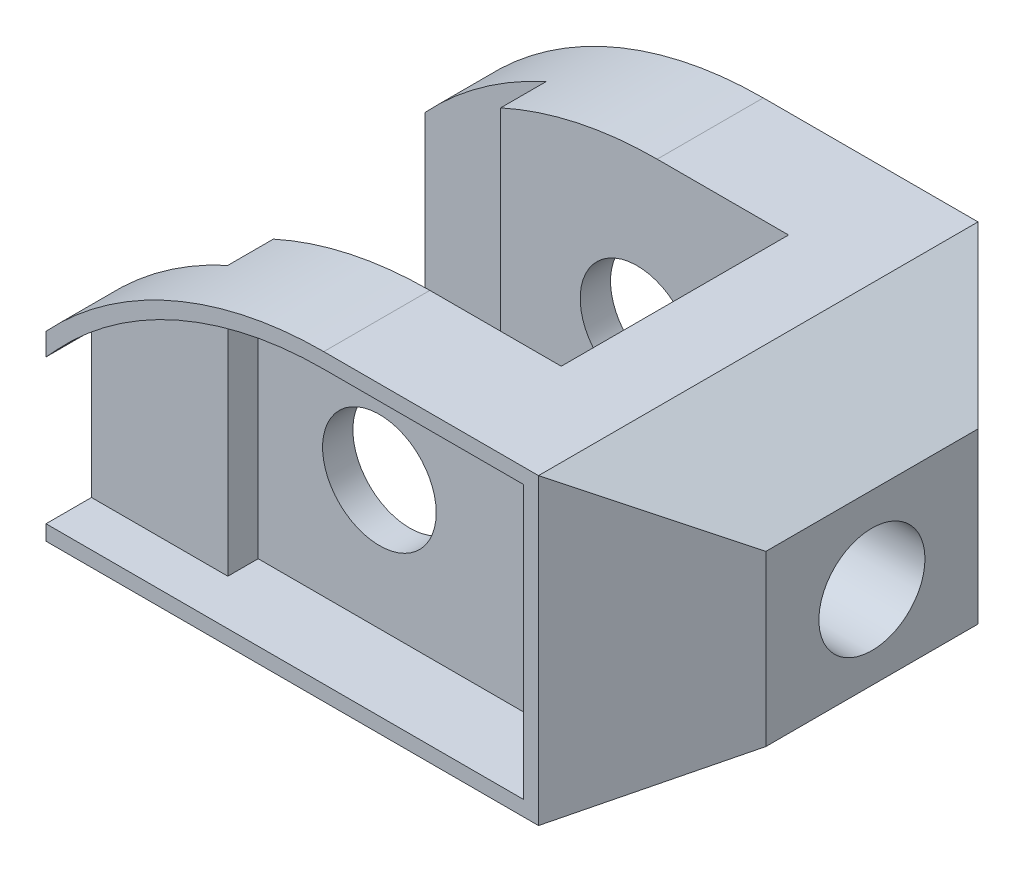
SolidWorks part; units mm, degrees
material "1060 Alloy"
ref_plane "Front Plane" through (0, 0, 0) normal (0, 0, 1) x (1, 0, 0)
ref_plane "Top Plane" through (0, 0, 0) normal (0, 1, 0) x (1, 0, 0)
ref_plane "Right Plane" through (0, 0, 0) normal (1, 0, 0) x (0, 0, -1)
sketch "Sketch2" plane through (0, 0, 0) normal (0, 0, 1) x (1, 0, 0)
  line L0 (0, 0) -> (65, 0)
  line L1 (65, 0) -> (80, 9.0293)
  line L2 (80, 9.0293) -> (80, 31.3397)
  line L3 (80, 31.3397) -> (65, 40)
  line L4 (65, 40) -> (36.6606, 40)
  line L5 (0, 0) -> (0, 24)
  arc A0 (0, 24) -> (36.6606, 40) centre (36.6606, -10) cw
  dimension "D5" = 50
  dimension "D1" = 65
  dimension "D2" = 40
  dimension "D3" = 30
  dimension "D4" = 31.046
  dimension "D6" = 24
  dimension "D7" = 15
  dimension "D8" = 15
extrude "Boss-Extrude1" add sketch "Sketch2" against normal blind 58
sketch "Sketch3" plane through (0, 0, 0) normal (0, 0, 1) x (1, 0, 0)
  line L0 (0, 0) -> (65, 0) construction
  circle A0 centre (34, 19) radius 7.5
  dimension "D3" = 15
  dimension "D1" = 19
  dimension "D2" = 31
extrude "Cut-Extrude1" cut sketch "Sketch3" against normal through all
sketch "Sketch4" plane through (0, 0, 0) normal (0, 1, 0) x (1, 0, 0)
  line L0 (65, 58) -> (80, 43)
  line L1 (80, 58) -> (80, 0) construction
  line L2 (80, 29) -> (65, 29) construction
  line L3 (65, 58) -> (65, 0) construction
  line L4 (65, 58) -> (80, 58)
  line L5 (80, 58) -> (80, 43)
  line L6 (65, 58) -> (36.6606, 58) construction
  line L7 (80, 0) -> (80, 15)
  line L8 (65, 0) -> (80, 15)
  line L9 (65, 0) -> (80, 0)
  dimension "D1" = 45
extrude "Cut-Extrude2" cut sketch "Sketch4" along normal through all
sketch "Sketch5" plane through (0, 0, 0) normal (0, -1, 0) x (1, 0, 0)
  line L0 (0, -8) -> (0, -50)
  line L1 (0, -58) -> (0, 0) construction
  line L2 (0, -8) -> (16, -8)
  line L3 (16, -8) -> (16, -14)
  line L4 (16, -14) -> (54, -14)
  line L5 (54, -14) -> (54, -44)
  line L6 (65, -29) -> (0, -29) construction
  line L7 (65, -58) -> (65, 0) construction
  line L8 (0, 0) -> (65, 0) construction
  line L9 (16, -50) -> (16, -44)
  line L10 (16, -44) -> (54, -44)
  line L11 (0, -50) -> (16, -50)
  point P17 (54, -29)
  dimension "D1" = 8
  dimension "D2" = 6
  dimension "D3" = 16
  dimension "D4" = 11
extrude "Cut-Extrude3" cut sketch "Sketch5" against normal through all
sketch "Sketch6" plane through (80, 0, 0) normal (1, 0, 0) x (0, 0, -1)
  line L0 (58, 0) -> (0, 0) construction
  line L1 (0, 40) -> (0, 0) construction
  circle A0 centre (29, 20) radius 7
  dimension "D3" = 14
  dimension "D1" = 20
  dimension "D2" = 29
extrude "Cut-Extrude4" cut sketch "Sketch6" against normal through all
sketch "Sketch8" plane through (0, 0, 0) normal (0, 0, 1) x (1, 0, 0)
  line L3 (1.4664, 22.64) -> (0, 21.0588)
  line L4 (0, 24) -> (0, 0) construction
  line L5 (0, 21.0588) -> (0, 2)
  line L6 (0, 2) -> (63, 2)
  line L7 (63, 2) -> (63, 38)
  line L8 (63, 38) -> (36.6606, 38)
  line L9 (0, 2) -> (63, 2)
  line L10 (63, 2) -> (63, 38)
  line L11 (63, 38) -> (36.6606, 38)
  arc A2 (36.6606, 38) -> (1.4664, 22.64) centre (36.6606, -10) ccw
  arc A3 (36.6606, 38) -> (1.4664, 22.64) centre (36.6606, -10) ccw
  point P0 (0, 0)
  dimension "D1" = 2
extrude "Cut-Extrude5" cut sketch "Sketch8" against normal blind 6
sketch "Sketch9" plane through (0, 0, -6) normal (0, 0, 1) x (1, 0, 0)
  line L0 (18, 2) -> (63, 2)
  line L1 (0, 2) -> (63, 2) construction
  line L2 (63, 2) -> (63, 38)
  line L3 (63, 38) -> (36.6606, 38)
  line L4 (18, 2) -> (18, 34.2242)
  arc A0 (36.6606, 38) -> (1.4664, 22.64) centre (36.6606, -10) ccw construction
  arc A1 (18, 34.2242) -> (36.6606, 38) centre (36.6606, -10) cw
  dimension "D1" = 45
extrude "Cut-Extrude6" cut sketch "Sketch9" against normal blind 4
sketch "Sketch10" plane through (0, 0, -58) normal (0, 0, -1) x (-1, 0, 0)
  line L3 (-1.4664, 22.64) -> (0, 21.0588)
  line L4 (0, 21.0588) -> (0, 2)
  line L6 (-63, 2) -> (0, 2)
  line L7 (-63, 38) -> (-63, 2)
  line L8 (-36.6606, 38) -> (-63, 38)
  line L9 (-63, 2) -> (0, 2)
  line L10 (-63, 38) -> (-63, 2)
  line L11 (-36.6606, 38) -> (-63, 38)
  arc A2 (-1.4664, 22.64) -> (-36.6606, 38) centre (-36.6606, -10) ccw
  arc A3 (-1.4664, 22.64) -> (-36.6606, 38) centre (-36.6606, -10) ccw
  dimension "D1" = 2
extrude "Cut-Extrude7" cut sketch "Sketch10" against normal blind 6
sketch "Sketch11" plane through (0, 0, -52) normal (0, 0, -1) x (-1, 0, 0)
  line L0 (-63, 38) -> (-63, 2)
  line L1 (-63, 2) -> (-18, 2)
  line L2 (-63, 2) -> (0, 2) construction
  line L3 (-18, 2) -> (-18, 34.2242)
  line L4 (-63, 38) -> (-36.6606, 38)
  arc A0 (-1.4664, 22.64) -> (-36.6606, 38) centre (-36.6606, -10) ccw construction
  arc A1 (-36.6606, 38) -> (-18, 34.2242) centre (-36.6606, -10) cw
  dimension "D1" = 45
extrude "Cut-Extrude8" cut sketch "Sketch11" against normal blind 4
equation "\"A\"= 58"
equation "\"B\"= 40"
equation "\"C\"= 65"
